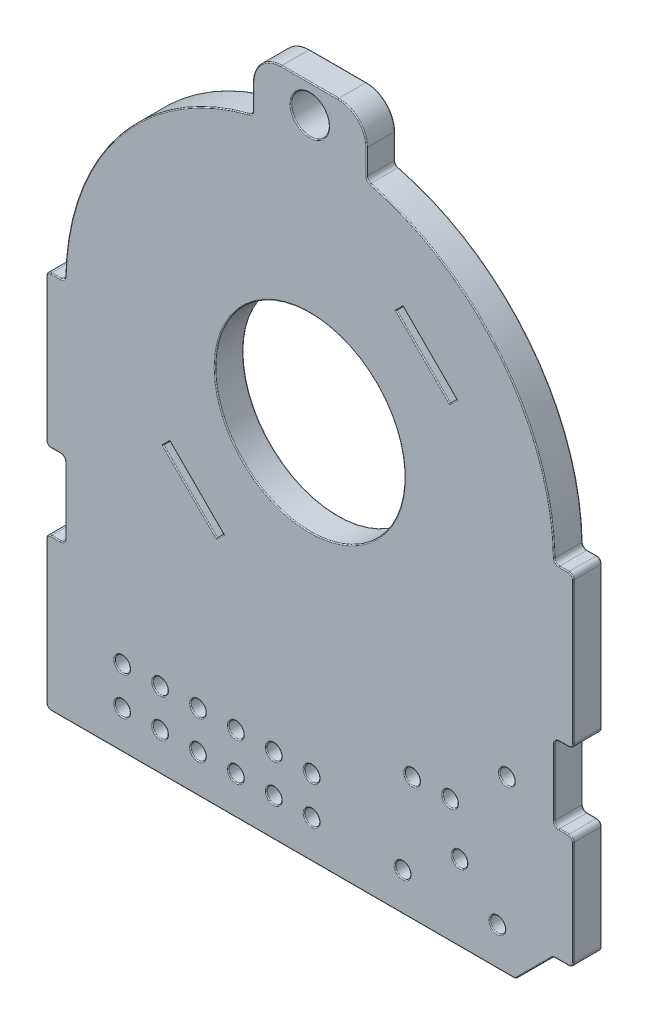
SolidWorks part; units mm, degrees
ref_plane "Ön Düzlem" through (0, 0, 0) normal (0, 0, 1) x (1, 0, 0)
ref_plane "Üst Düzlem" through (0, 0, 0) normal (0, 1, 0) x (1, 0, 0)
ref_plane "Sağ Düzlem" through (0, 0, 0) normal (1, 0, 0) x (0, 0, -1)
sketch "Sketch1" plane through (0, 0, 0) normal (0, 0, 1) x (1, 0, 0)
  line L0 (13.1476, 0) -> (13.65, 0)
  line L1 (-13.65, 0) -> (-13.1476, 0)
  line L2 (-13.9, -0.25) -> (-13.9, -7.75)
  line L3 (-13.65, -20) -> (10.7418, -20)
  line L4 (13.9, -0.25) -> (13.9, -7.75)
  line L5 (0, 15.5463) -> (0, 12.9) construction
  line L6 (-3, 12.7421) -> (-3, 14.0463)
  line L7 (0, -20) -> (0, 12.9) construction
  line L8 (12.7722, -18.0732) -> (10.9186, -19.9268)
  line L9 (13.65, -18) -> (12.949, -18)
  line L10 (13.9, -12.25) -> (13.9, -17.75)
  line L11 (13.65, -8) -> (13.15, -8)
  line L12 (-13.65, -12) -> (-13.15, -12)
  line L13 (13.65, -12) -> (13.15, -12)
  line L14 (12.9, -8.25) -> (12.9, -11.75)
  line L15 (-12.9, -8.25) -> (-12.9, -11.75)
  line L16 (-13.65, -8) -> (-13.15, -8)
  line L17 (-13.9, -12.25) -> (-13.9, -19.75)
  line L18 (-1.5, 15.5463) -> (1.5, 15.5463)
  line L19 (3, 14.0463) -> (3, 12.7421)
  line L20 (3, 14.0463) -> (-3, 14.0463) construction
  arc A0 (12.8977, 0.2452) -> (3.1882, 12.4998) centre (0, 0) ccw
  arc A1 (-12.8977, 0.2452) -> (-13.1476, 0) centre (-13.1476, 0.25) cw
  arc A2 (-13.65, 0) -> (-13.9, -0.25) centre (-13.65, -0.25) ccw
  arc A3 (12.8977, 0.2452) -> (13.1476, 0) centre (13.1476, 0.25) ccw
  arc A4 (13.65, 0) -> (13.9, -0.25) centre (13.65, -0.25) cw
  arc A5 (13.65, -18) -> (13.9, -17.75) centre (13.65, -17.75) ccw
  arc A6 (12.7722, -18.0732) -> (12.949, -18) centre (12.949, -18.25) cw
  arc A7 (10.9186, -19.9268) -> (10.7418, -20) centre (10.7418, -19.75) cw
  arc A8 (-13.65, -20) -> (-13.9, -19.75) centre (-13.65, -19.75) cw
  arc A9 (-3.1882, 12.4998) -> (-12.8977, 0.2452) centre (0, 0) ccw
  arc A10 (-3.1882, 12.4998) -> (-3, 12.7421) centre (-3.25, 12.7421) ccw
  circle A11 centre (0, 0) radius 12.9 construction
  arc A12 (-13.65, -8) -> (-13.9, -7.75) centre (-13.65, -7.75) cw
  arc A13 (-13.65, -12) -> (-13.9, -12.25) centre (-13.65, -12.25) ccw
  arc A14 (-13.15, -12) -> (-12.9, -11.75) centre (-13.15, -11.75) ccw
  arc A15 (-12.9, -8.25) -> (-13.15, -8) centre (-13.15, -8.25) ccw
  arc A16 (13.15, -8) -> (12.9, -8.25) centre (13.15, -8.25) ccw
  arc A17 (13.65, -8) -> (13.9, -7.75) centre (13.65, -7.75) ccw
  arc A18 (13.15, -12) -> (12.9, -11.75) centre (13.15, -11.75) cw
  arc A19 (13.9, -12.25) -> (13.65, -12) centre (13.65, -12.25) ccw
  circle A20 centre (10.4, -11) radius 0.4
  circle A21 centre (7.9, -16) radius 0.4
  circle A22 centre (9.9, -18) radius 0.4
  circle A23 centre (4.9, -18) radius 0.4
  circle A24 centre (7.4, -13.5) radius 0.4
  circle A25 centre (5.4, -13.5) radius 0.4
  arc A26 (3.1882, 12.4998) -> (3, 12.7421) centre (3.25, 12.7421) cw
  arc A27 (-3, 14.0463) -> (-1.5, 15.5463) centre (-1.5, 14.0463) cw
  arc A28 (1.5, 15.5463) -> (3, 14.0463) centre (1.5, 14.0463) cw
  circle A29 centre (0, 14.0463) radius 1
  circle A30 centre (0.1, -18) radius 0.4
  circle A31 centre (-1.9, -18) radius 0.4
  circle A32 centre (-3.9, -18) radius 0.4
  circle A33 centre (-5.9, -18) radius 0.4
  circle A34 centre (-7.9, -18) radius 0.4
  circle A35 centre (-9.9, -18) radius 0.4
  circle A36 centre (-1.9, -16) radius 0.4
  circle A37 centre (-3.9, -16) radius 0.4
  circle A38 centre (-5.9, -16) radius 0.4
  circle A39 centre (-7.9, -16) radius 0.4
  circle A40 centre (-9.9, -16) radius 0.4
  circle A41 centre (0.1, -16) radius 0.4
  point P18 (-13.9, 0)
  point P21 (12.9, 0)
  point P26 (13.9, -18)
  point P29 (12.8454, -18)
  point P32 (10.8454, -20)
  point P39 (-3, 12.5463)
  point P53 (-13.9, -8)
  point P56 (-13.9, -12)
  point P59 (-12.9, -12)
  point P62 (-12.9, -8)
  point P65 (12.9, -8)
  point P68 (13.9, -8)
  point P71 (12.9, -12)
  point P74 (13.9, -12)
  point P87 (3, 12.5463)
  point P92 (3, 15.5463)
  dimension "D1" = 25.8
  dimension "D4" = 0.25
  dimension "D11" = 0.25
  dimension "D12" = 0.8
  dimension "D13" = 2.5
  dimension "D14" = 9
  dimension "D15" = 0.8
  dimension "D16" = 0.8
  dimension "D17" = 0.8
  dimension "D18" = 2
  dimension "D19" = 2
  dimension "D20" = 5
  dimension "D21" = 4
  dimension "D22" = 4
  dimension "D23" = 2
  dimension "D24" = 0.8
  dimension "D25" = 0.8
  dimension "D26" = 2
  dimension "D27" = 6.5
  dimension "D28" = 0
  dimension "D5" = 0.25
  dimension "D29" = 0.25
  dimension "D30" = 1.5
  dimension "D32" = 2
  dimension "D33" = 0.8
  dimension "D36" = 2
  dimension "D37" = 4
  dimension "D38" = 6.5
  dimension "D2" = 13.9
  dimension "D3" = 13.9
  dimension "D6" = 3
  dimension "D7" = 3
  dimension "D8" = 8
  dimension "D9" = 4
  dimension "D10" = 1
  dimension "D31" = 1.5
  dimension "D35" = 6
  dimension "D34" = 2
extrude "Boss-Extrude1" add sketch "Sketch1" along normal blind 1.5
sketch "Sketch2" plane through (0, 0, 1.5) normal (0, 0, 1) x (1, 0, 0)
  line L0 (-12.9, 0) -> (12.9, 0) construction
  line L2 (4.5608, 7.3893) -> (4.9144, 7.7428)
  line L3 (7.3893, 4.5608) -> (4.5608, 7.3893)
  line L4 (7.7428, 4.9144) -> (7.3893, 4.5608)
  line L5 (-9.1217, -9.1217) -> (9.0267, 9.0267) construction
  line L6 (4.9144, 7.7428) -> (7.7428, 4.9144)
  line L10 (-7.7428, -4.9144) -> (-4.9144, -7.7428)
  line L11 (-4.9144, -7.7428) -> (-4.5608, -7.3893)
  line L12 (-4.5608, -7.3893) -> (-7.3893, -4.5608)
  line L13 (-7.3893, -4.5608) -> (-7.7428, -4.9144)
  circle A0 centre (0, 0) radius 5
  circle A1 centre (0, 0) radius 12.9 construction
  dimension "D1" = 10
  dimension "D2" = 16.9
  dimension "D3" = 8.45
  dimension "D6" = 4
  dimension "D7" = 0.5
  dimension "D8" = 2
  dimension "D10" = 45
  dimension "D11" = 0
extrude "Cut-Extrude1" cut sketch "Sketch2" against normal through all
fillet "Fillet1" radius 0.05 54 edges at (10.111, 8.0111, 1.5) (6.3286, 6.3286, 1.5) (4.7376, 7.566, 1.5) (-6.3286, -6.3286, 1.5) (-4.7376, -7.566, 1.5) (-5.9751, -5.9751, 1.5) (-7.566, -4.7376, 1.5) (13.3988, 0, 0) (13.9, -4, 1.5) (-1.4541, -20, 1.5) (-13.9, -4, 1.5) (13.2995, -18, 0) (13.2995, -18, 1.5) (-13.8268, -0.0732, 0) (10.8375, -19.981, 0) (12.8533, -18.019, 0) (13.8268, -17.9268, 0) (13.8268, -0.0732, 0) (12.9725, 0.0716, 1.5) (12.8533, -18.019, 1.5) (-13.4, -8, 0) (-12.9, -10, 0) (-13.4, -12, 0) (-13.9, -16, 0) (13.4, -12, 0) (12.9, -10, 0) (13.4, -8, 0) (12.9, -10, 1.5) (-13.9, -16, 1.5) (-13.8268, -7.9268, 0) (-12.9732, -8.0732, 0) (-13.8268, -12.0732, 0) (13.8268, -7.9268, 0) (13.8268, -7.9268, 1.5) (12.9732, -8.0732, 1.5) (-12.9732, -11.9268, 1.5) (-13.8268, -7.9268, 1.5) (8.3, -16, 1.5) (10.3, -18, 1.5) (5.8, -13.5, 1.5) (-13.8268, -19.9268, 0) (0, 15.5463, 0) (-3, 13.3942, 0) (-10.111, 8.0111, 1.5) (-3.0526, 12.5887, 1.5) (3, 13.3942, 1.5) (3.0526, 12.5887, 1.5) (-3.5, -16, 1.5) (-9.5, -18, 1.5) (-5.5, -18, 1.5) (-1.5, -18, 1.5) (-3.5, -18, 1.5) (-7.5, -18, 1.5) (-5.5, -16, 1.5)
